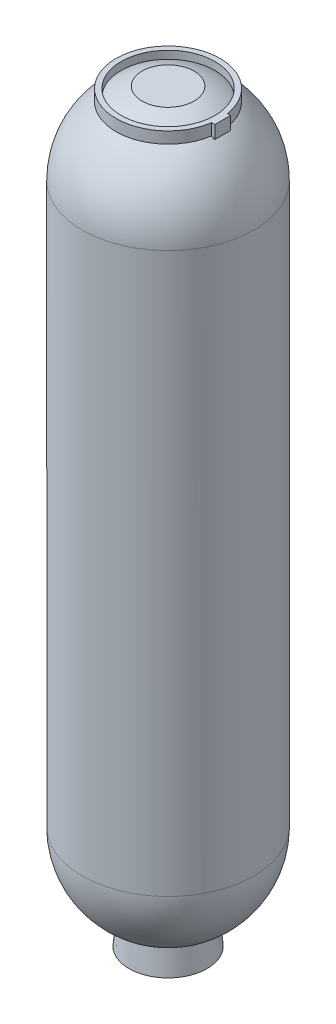
SolidWorks part; units mm, degrees
material "Кедр"
ref_plane "Спереди" through (0, 0, 0) normal (0, 0, 1) x (1, 0, 0)
ref_plane "Сверху" through (0, 0, 0) normal (0, 1, 0) x (1, 0, 0)
ref_plane "Справа" through (0, 0, 0) normal (1, 0, 0) x (0, 0, -1)
sketch "Профиль" plane through (0, 0, 0) normal (0, 0, 1) x (1, 0, 0)
  line L0 (0, 0) -> (0, 5.4272) construction
  line L1 (15, 0) -> (13, 0)
  line L2 (13, 0) -> (6, 10)
  line L3 (6, 10) -> (0, 10)
  line L4 (15, 0) -> (14.067, 10)
  line L5 (33, 39.8516) -> (33, 254.8516)
  line L6 (10, 286.3) -> (0, 286.3)
  line L7 (0, 286.3) -> (0, 10)
  line L8 (18, 282.5103) -> (18, 285.5103)
  line L9 (18, 285.5103) -> (20, 285.5103)
  line L10 (20, 285.5103) -> (20, 281.1004)
  arc A0 (14.067, 10) -> (33, 39.8516) centre (0, 39.8516) ccw
  arc A1 (33, 254.8516) -> (20, 281.1004) centre (0, 254.8516) ccw
  arc A2 (18, 282.5103) -> (10, 286.3) centre (0, 254.8516) ccw
  point P14 (5, 286.3)
  dimension "D6" = 33
  dimension "D8" = 33
  dimension "D1" = 33
  dimension "D2" = 286.3
  dimension "D3" = 10
  dimension "D4" = 15
  dimension "D5" = 13
  dimension "D7" = 10
  dimension "D9" = 6
  dimension "D10" = 215
  dimension "D11" = 20
  dimension "D12" = 2
  dimension "D13" = 3
revolve "Повернуть" add sketch "Профиль" angle 360 about L0
sketch "Эскиз2" plane through (0, 285.5103, 0) normal (0, 1, 0) x (1, 0, 0)
  line L0 (18, 3) -> (21, 3)
  line L1 (21, 3) -> (21, -3)
  line L2 (21, -3) -> (18, -3)
  line L3 (18, -3) -> (18, 3)
  line L4 (0, 0) -> (18, 0) construction
  dimension "D1" = 6
  dimension "D2" = 3
  dimension "D3" = 18
extrude "Контакты запала" add sketch "Эскиз2" against normal blind 5
